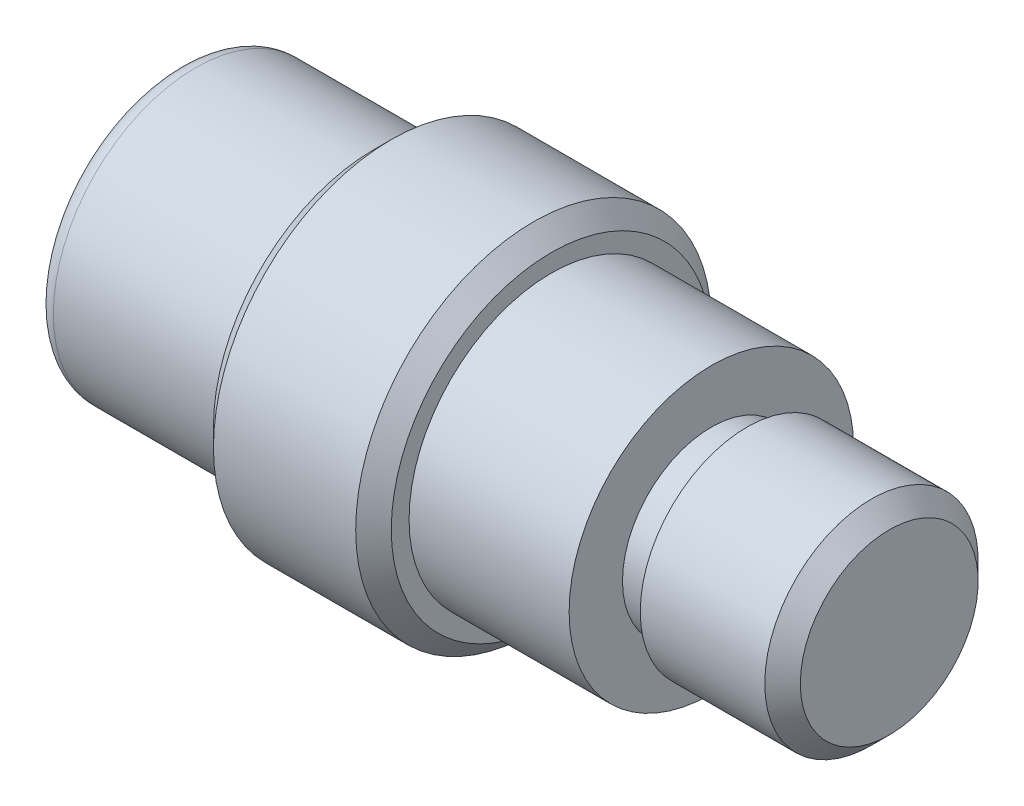
SolidWorks part; units mm, degrees
ref_plane "前视基准面" through (0, 0, 0) normal (0, 0, 1) x (1, 0, 0)
ref_plane "上视基准面" through (0, 0, 0) normal (0, 1, 0) x (1, 0, 0)
ref_plane "右视基准面" through (0, 0, 0) normal (1, 0, 0) x (0, 0, -1)
sketch "草图1" plane through (0, 0, 0) normal (0, 0, 1) x (1, 0, 0)
  line L0 (0, 0) -> (0, 7)
  line L1 (1, 8) -> (11, 8)
  line L2 (11, 8) -> (11, 10)
  line L3 (11, 10) -> (21, 10)
  line L4 (21, 10) -> (21, 8)
  line L5 (21, 8) -> (30, 8)
  line L6 (30, 8) -> (30, 5)
  line L7 (30, 5) -> (32, 5)
  line L8 (40, 6) -> (40, 0)
  line L9 (0, 0) -> (40, 0)
  line L10 (32, 5) -> (32, 6)
  line L11 (32, 6) -> (40, 6)
  arc A0 (1, 8) -> (0, 7) centre (1, 7) ccw
  dimension "D1" = 8
  dimension "D2" = 10
  dimension "D3" = 2
  dimension "D4" = 10
  dimension "D5" = 40
  dimension "D6" = 2
  dimension "D7" = 10
  dimension "D8" = 3
  dimension "D9" = 10
  dimension "D10" = 1
revolve "旋转1" add sketch "草图1" angle 360 about L9
cosmetic thread "装饰螺纹线1"
chamfer "倒角1" distance 1 angle 45 2 edges at (21, 0, 10) (11, 0, 10)
chamfer "倒角2" distance 1 angle 45 1 edges at (40, 0, 6)
